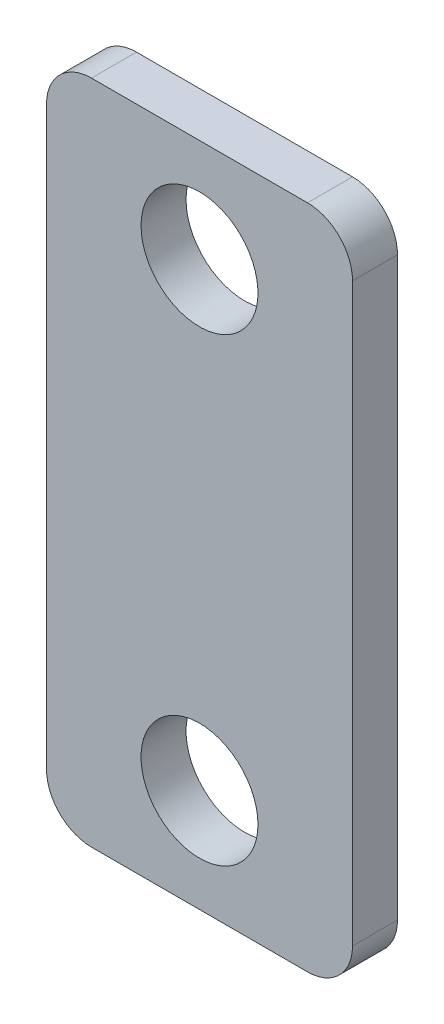
SolidWorks part; units mm, degrees
material "3003 Alloy"
ref_plane "X-Y Datum" through (0, 0, 0) normal (0, 0, 1) x (1, 0, 0)
ref_plane "X-Z Datum" through (0, 0, 0) normal (0, 1, 0) x (1, 0, 0)
ref_plane "Y-Z Datum" through (0, 0, 0) normal (1, 0, 0) x (0, 0, -1)
sketch "Sketch1" plane through (0, 0, 0) normal (0, 0, 1) x (1, 0, 0)
  line L0 (10.795, -5.0855) -> (10.795, -7.7372) construction
  line L1 (0, 0) -> (21.59, 0)
  line L2 (0, 0) -> (0, 46.99)
  line L3 (0, 46.99) -> (21.59, 46.99)
  line L4 (21.59, 0) -> (21.59, 46.99)
  line L5 (0, 23.495) -> (19.6604, 23.495) construction
  circle A0 centre (10.795, 7.2602) radius 4.125
  circle A1 centre (10.795, 39.7298) radius 4.125
  dimension "D1" = 46.99
extrude "Boss-Extrude1" add sketch "Sketch1" along normal blind 3.175 contours L0 A0 | A0 L0 | L3 L4 L1 L2 | A1
fillet "Fillet1" radius 3.175 4 edges at (21.59, 46.99, 1.5875) (0, 46.99, 1.5875) (0, 0, 1.5875) (21.59, 0, 1.5875)
